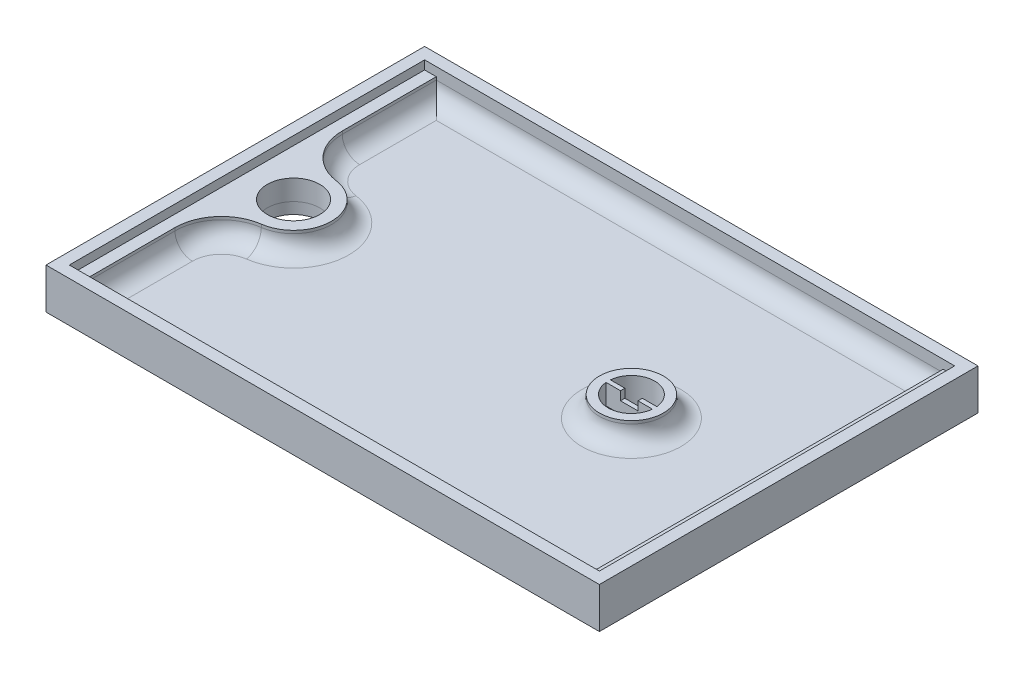
SolidWorks part; units mm, degrees
ref_plane "Front Plane" through (0, 0, 0) normal (0, 0, 1) x (1, 0, 0)
ref_plane "Top Plane" through (0, 0, 0) normal (0, 1, 0) x (1, 0, 0)
ref_plane "Right Plane" through (0, 0, 0) normal (1, 0, 0) x (0, 0, -1)
sketch "Master_Geometry" plane through (0, 0, 0) normal (0, 0, 1) x (1, 0, 0)
  line L0 (0, 6.611) -> (0, -8.3361) construction
  line L1 (-45, -1) -> (45, -1) construction
  line L2 (-45, -1) -> (-45, 1) construction
  line L3 (-45, 1) -> (45, 1) construction
  line L4 (45, -1) -> (45, 1) construction
  line L5 (-45, -1) -> (45, 1) construction
  line L6 (-45, 1) -> (45, -1) construction
  line L7 (-47.5, -5) -> (-47.5, 0)
  line L8 (-47.5, -7) -> (47.5, -7)
  line L9 (-47.5, -7) -> (-47.5, -5)
  line L10 (-43.5, -5) -> (43.5, -5)
  line L11 (47.5, -7) -> (47.5, -5)
  line L12 (43.5, -1.5) -> (43.5, -5)
  line L13 (45.5, -1.5) -> (43.5, -1.5)
  line L14 (-47.5, 0) -> (-45.5, 0)
  line L15 (-45.5, 0) -> (-45.5, -1.5)
  line L16 (-45.5, -1.5) -> (-43.5, -1.5)
  line L17 (-43.5, -1.5) -> (-43.5, -5)
  line L18 (45.5, 0) -> (45.5, -1.5)
  line L19 (47.5, 0) -> (45.5, 0)
  line L20 (47.5, -5) -> (47.5, 0)
  point P0 (0, 0)
  point P7 (0, -6)
  dimension "D1" = 90
  dimension "D2" = 2
  dimension "D3" = 4
  dimension "D4" = 2
  dimension "D6" = 7
  dimension "D7" = 3.5
  dimension "D8" = 2
  dimension "D9" = 2
  dimension "D5" = 0.5
extrude "PCB_Stand" add sketch "Master_Geometry" along normal mid plane 61
ref_plane "PCB_Midplane_A" through (0, 0, 0) normal (1, 0, 0) x (0, 0, -1)
ref_plane "PCB_Midplane_B" through (0, 0, 0) normal (0, 0, 1) x (1, 0, 0)
sketch "Sketch3" plane through (0, 0, 30.5) normal (0, 0, 1) x (1, 0, 0)
  line L0 (-47.5, 0) -> (-47.5, -7)
  line L1 (-47.5, -7) -> (47.5, -7)
  line L2 (47.5, -7) -> (47.5, 0)
  line L3 (47.5, 0) -> (-47.5, 0)
extrude "Extra_Bottom" add sketch "Sketch3" along normal blind 2
mirror "Mirror2" about plane through (0, 0, 0) normal (0, 0, 1) of "Extra_Bottom"
sketch "Sensor-Holes" plane through (0, -7, 0) normal (0, -1, 0) x (1, 0, 0)
  line L0 (-47.5, 32.5) -> (-47.5, -32.5) construction
  line L3 (55, 0) -> (-55, 0) construction
  circle A0 centre (-37.5, 0) radius 4.6
  circle A1 centre (20.5, 0) radius 4
  dimension "D4" = 9.2
  dimension "D5" = 8
  dimension "D1" = 58
  dimension "D2" = 10
extrude "Sensor_Holes" cut sketch "Sensor-Holes" against normal through all
sketch "Sketch4" plane through (0, -5, 0) normal (0, 1, 0) x (1, 0, 0)
  line L1 (-43.5, -30.5) -> (-43.5, 30.5) construction
  line L2 (-55, 0) -> (55, 0) construction
  line L3 (-43.5, 14.3614) -> (-43.5, -14.3614)
  line L4 (16.5176, 0.375) -> (24.4824, 0.375)
  line L5 (16.5176, -0.375) -> (24.4824, -0.375)
  circle A0 centre (20.5, 0) radius 5.5
  circle A1 centre (-37.5, 0) radius 4.5
  circle A2 centre (20.5, 0) radius 4 construction
  circle A3 centre (-37.5, 0) radius 4.6 construction
  arc A4 (16.5176, -0.375) -> (24.4824, -0.375) centre (20.5, 0) ccw
  arc A5 (-36.6034, -6.4379) -> (-36.6034, 6.4379) centre (-37.5, 0) ccw
  arc A6 (-36.6034, -6.4379) -> (-43.5, -14.3614) centre (-35.5, -14.3614) ccw
  arc A7 (-36.6034, 6.4379) -> (-43.5, 14.3614) centre (-35.5, 14.3614) cw
  arc A8 (24.4824, 0.375) -> (16.5176, 0.375) centre (20.5, 0) ccw
  dimension "D4" = 2
  dimension "D1" = 11
  dimension "D2" = 9
  dimension "D3" = 16
  dimension "D5" = 0.75
  dimension "D6" = 0.375
extrude "Sensor_Stands" add sketch "Sketch4" along normal up to surface (3.5 mm away) up to face at (-44.5, -1.5, 0)
fillet "Fillet1" radius 3 9 edges at (-43.5, -5, 22.4307) (-41.5344, -5, 9.1091) (-43.5, -5, -22.4307) (-41.5344, -5, -9.1091) (-31, -5, 0) (20.5, -5, -5.5) (43.5, -5, 0) (0, -5, 30.5) (0, -5, -30.5)
sketch "Sketch5" plane through (0, -1.5, 0) normal (0, 1, 0) x (1, 0, 0)
  line L0 (-55, 0) -> (55, 0) construction
  line L1 (19, -0.375) -> (22, -0.375)
  line L2 (19, -0.375) -> (19, 0.375)
  line L3 (19, 0.375) -> (22, 0.375)
  line L4 (22, -0.375) -> (22, 0.375)
  line L5 (19, -0.375) -> (22, 0.375) construction
  line L6 (19, 0.375) -> (22, -0.375) construction
  line L7 (24.4824, 0.375) -> (16.5176, 0.375) construction
  circle A0 centre (20.5, 0) radius 5.5 construction
  circle A2 centre (20.5, 0) radius 5.5 construction
  circle A4 centre (20.5, 0) radius 5.5 construction
  point P0 (20.5, 0)
  dimension "D1" = 3
extrude "ToF_Slot" cut sketch "Sketch5" against normal blind 1.5
sketch "Reference_Geom_IR" plane through (0, -7, 0) normal (0, -1, 0) x (1, 0, 0)
  circle A0 centre (-37.5, 0) radius 4.6 construction
  circle A2 centre (-37.5, 0) radius 4.6 construction
equation "\"pcb_length\"= 90mm"
equation "\"pcb_width\"= 60mm"
equation "\"pcb_depth\"= 2mm"
equation "\"rel_tol\"= 0.5mm"
equation "\"dist_pcb_bottom\"= 4mm"
equation "\"thickness_bottom\"= 2mm"
equation "\"dist_pcb_edge\"= 2mm"
equation "\"stair_length\"= 2mm"
equation "\"stair_height\"= \"dist_pcb_bottom\" - \"rel_tol\""
equation "\"D1@Master_Geometry\" = \"pcb_length\""
equation "\"D2@Master_Geometry\" = \"pcb_depth\""
equation "\"D3@Master_Geometry\" = \"dist_pcb_bottom\""
equation "\"D4@Master_Geometry\" = \"thickness_bottom\""
equation "\"height_bottom\"= 7mm"
equation "\"D6@Master_Geometry\" = \"height_bottom\""
equation "\"D7@Master_Geometry\" = \"stair_height\""
equation "\"D8@Master_Geometry\" = \"stair_length\""
equation "\"D9@Master_Geometry\" = \"dist_pcb_edge\""
equation "\"D5@Master_Geometry\" = \"rel_tol\""
equation "\"pcb_extra\"= 8mm"
equation "\"dist_ir_tof\"= 58mm"
equation "\"dist_tof_edge\"= 48mm"
equation "\"D1@Sensor-Holes\" = \"dist_ir_tof\""
equation "\"diameter_ir\"= 9.2mm"
equation "\"diameter_tof\"= 5mm"
equation "\"D5@Sensor-Holes\"=\"diameter_tof\"+3mm"
equation "\"D4@Sensor-Holes\"=\"diameter_ir\""
equation "\"D1@Sketch4\"=\"diameter_tof\"+6mm"
equation "\"D1\"= 5mm - \"rel_tol\""
equation "\"D2@Sketch4\"=\"diameter_tof\"+4mm"
equation "\"D1@PCB_Stand\"=\"pcb_width\"+2*\"rel_tol\""
